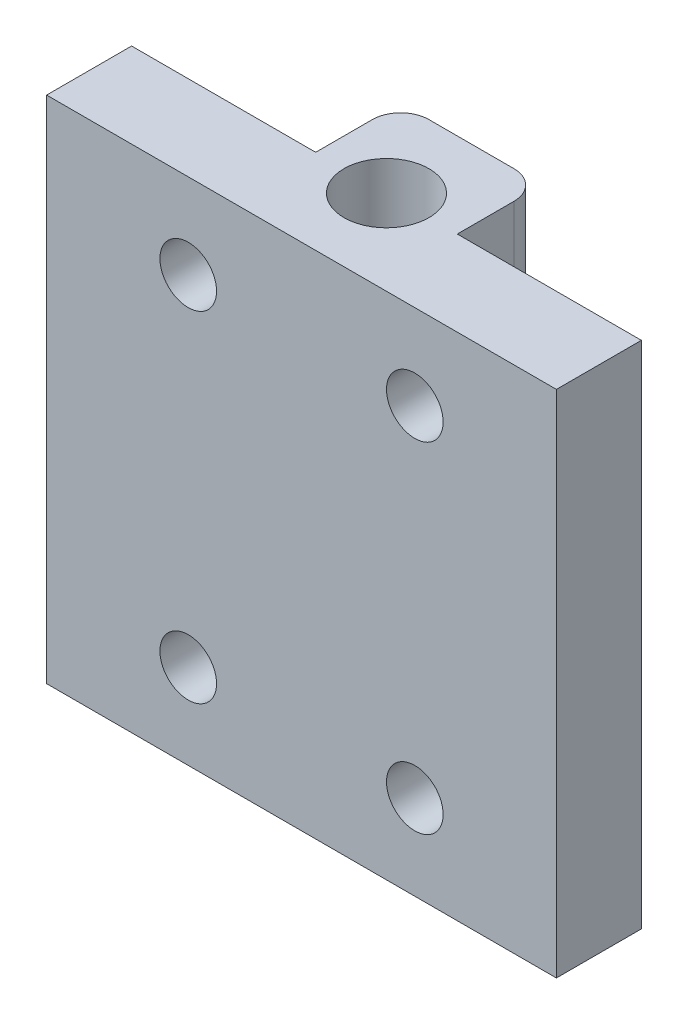
SolidWorks part; units mm, degrees
ref_plane "前视基准面" through (0, 0, 0) normal (0, 0, 1) x (1, 0, 0)
ref_plane "上视基准面" through (0, 0, 0) normal (0, 1, 0) x (1, 0, 0)
ref_plane "右视基准面" through (0, 0, 0) normal (1, 0, 0) x (0, 0, -1)
other "Configuration Table"
sketch "草图1" plane through (0, 0, 0) normal (0, 0, 1) x (1, 0, 0)
  line L1 (9, -9) -> (-9, -9)
  line L2 (9, -9) -> (9, 9)
  line L3 (9, 9) -> (-9, 9)
  line L4 (-9, -9) -> (-9, 9)
  line L5 (9, -9) -> (-9, 9) construction
  line L6 (9, 9) -> (-9, -9) construction
  point P0 (0, 0)
  dimension "D1" = 18
  dimension "D2" = 18
extrude "凸台-拉伸1" add sketch "草图1" along normal blind 3
sketch "草图4" plane through (0, 0, 3) normal (0, 0, 1) x (1, 0, 0)
  circle A0 centre (-4, -6) radius 1
  circle A1 centre (4, -6) radius 1
  circle A2 centre (4, 6) radius 1
  circle A3 centre (-4, 6) radius 1
  dimension "D1" = 2
  dimension "D2" = 2
  dimension "D3" = 2
  dimension "D4" = 2
extrude "切除-拉伸1" cut sketch "草图4" against normal through all
sketch "草图8" plane through (0, 9, 0) normal (0, 1, 0) x (1, 0, 0)
  line L0 (2.5, 0) -> (-2.5, 0)
  line L1 (9, 0) -> (-9, 0) construction
  line L2 (-2.5, 0) -> (-2.5, 3)
  line L3 (-2.5, 3) -> (2.5, 3)
  line L4 (2.5, 3) -> (2.5, 0)
  point P5 (0, 0)
  dimension "D1" = 5
  dimension "D2" = 3
extrude "凸台-拉伸4" add sketch "草图8" against normal up to surface (18 mm away) up to face at (0, -9, 1.5)
sketch "草图9" plane through (0, 9, 0) normal (0, 1, 0) x (1, 0, 0)
  circle A0 centre (0, 0) radius 1.5
  dimension "D1" = 3
extrude "切除-拉伸3" cut sketch "草图9" against normal through all
fillet "圆角3" radius 1 2 edges at (-2.5, 0, -3) (2.5, 0, -3)
